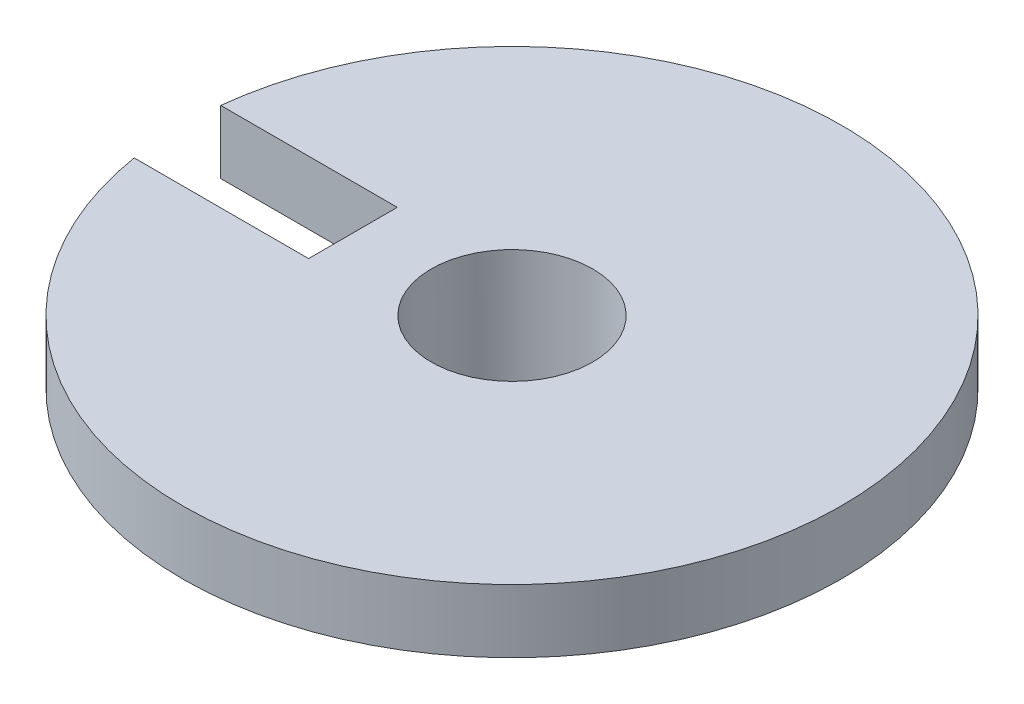
SolidWorks part; units mm, degrees
ref_plane "Front Plane" through (0, 0, 0) normal (0, 0, 1) x (1, 0, 0)
ref_plane "Top Plane" through (0, 0, 0) normal (0, 1, 0) x (1, 0, 0)
ref_plane "Right Plane" through (0, 0, 0) normal (1, 0, 0) x (0, 0, -1)
sketch "Sketch1" plane through (0, 0, 0) normal (0, 1, 0) x (1, 0, 0)
  circle A0 centre (0, 0) radius 5.685
  circle A1 centre (0, 0) radius 3.185
  dimension "D1" = 2.5
  dimension "D2" = 6.37
extrude "Boss-Extrude1" add sketch "Sketch1" along normal blind 4.46
sketch "Sketch2" plane through (0, 4.46, 0) normal (0, 1, 0) x (1, 0, 0)
  circle A0 centre (0, 0) radius 13
extrude "Boss-Extrude2" add sketch "Sketch2" along normal blind 2.5
sketch "Sketch3" plane through (0, 4.46, 0) normal (0, -1, 0) x (1, 0, 0)
  circle A0 centre (0, 0) radius 3.185
extrude "Cut-Extrude1" cut sketch "Sketch3" against normal blind 2.5
sketch "Sketch4" plane through (0, 4.46, 0) normal (0, -1, 0) x (1, 0, 0)
  line L1 (-14.4713, 2.068) -> (-5.9562, 2.068)
  line L2 (-14.4713, 2.068) -> (-14.4713, -1.432)
  line L3 (-14.4713, -1.432) -> (-5.9562, -1.432)
  line L4 (-5.9562, 2.068) -> (-5.9562, -1.432)
  dimension "D1" = 3.5
extrude "Cut-Extrude2" cut sketch "Sketch4" against normal blind 10
